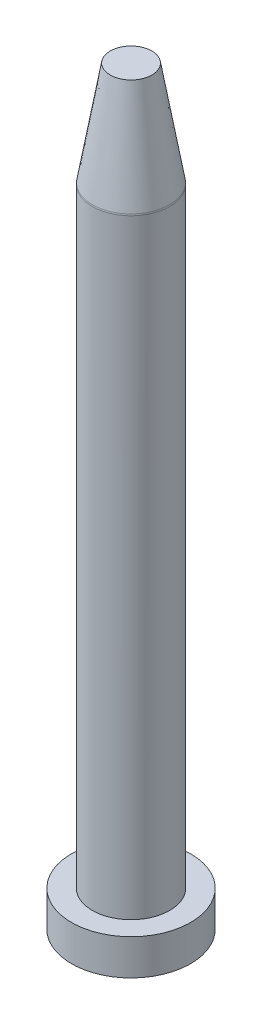
SolidWorks part; units mm, degrees
ref_plane "前视" through (0, 0, 0) normal (0, 0, 1) x (1, 0, 0)
ref_plane "上视" through (0, 0, 0) normal (0, 1, 0) x (1, 0, 0)
ref_plane "右视" through (0, 0, 0) normal (1, 0, 0) x (0, 0, -1)
sketch "草图1" plane through (0, 0, 0) normal (0, 0, 1) x (1, 0, 0)
  line L0 (0, 0) -> (0, 101.922) construction
  line L1 (0, 0) -> (20, 0)
  line L2 (20, 0) -> (20, 12)
  line L3 (20, 12) -> (13, 12)
  line L4 (13, 12) -> (13, 217)
  line L5 (0, 252) -> (7, 252)
  line L6 (7, 252) -> (13, 217)
  line L7 (0, 0) -> (0, 252)
  point P7 (0, 252)
  dimension "D1" = 20
  dimension "D2" = 12
  dimension "D3" = 7
  dimension "D4" = 205
  dimension "D5" = 252
  dimension "D6" = 7
revolve "基体-旋转" add sketch "草图1" angle 360 about L0
fillet "圆角1" radius 3 1 edges at (0, 217, -13)
